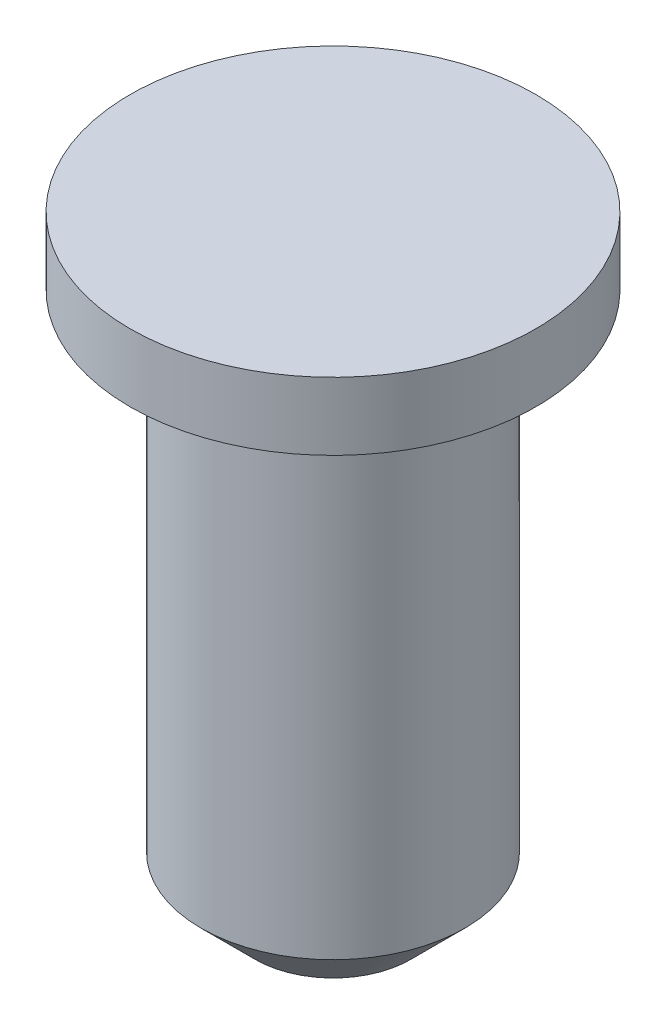
SolidWorks part; units mm, degrees
ref_plane "Front Plane" through (0, 0, 0) normal (0, 0, 1) x (1, 0, 0)
ref_plane "Top Plane" through (0, 0, 0) normal (0, 1, 0) x (1, 0, 0)
ref_plane "Right Plane" through (0, 0, 0) normal (1, 0, 0) x (0, 0, -1)
sketch "Sketch1" plane through (0, 0, 0) normal (0, 1, 0) x (1, 0, 0)
  circle A0 centre (0, 0) radius 1.95
  dimension "D1" = 3.9
extrude "Boss-Extrude3" add sketch "Sketch1" along normal blind 8
sketch "Sketch3" plane through (0, 8, 0) normal (0, 1, 0) x (1, 0, 0)
  circle A0 centre (0, 0) radius 3
  dimension "D1" = 6
extrude "Boss-Extrude4" add sketch "Sketch3" along normal blind 1
chamfer "Chamfer1" distance 0.8 angle 45 1 edges at (0, 0, 1.95)
